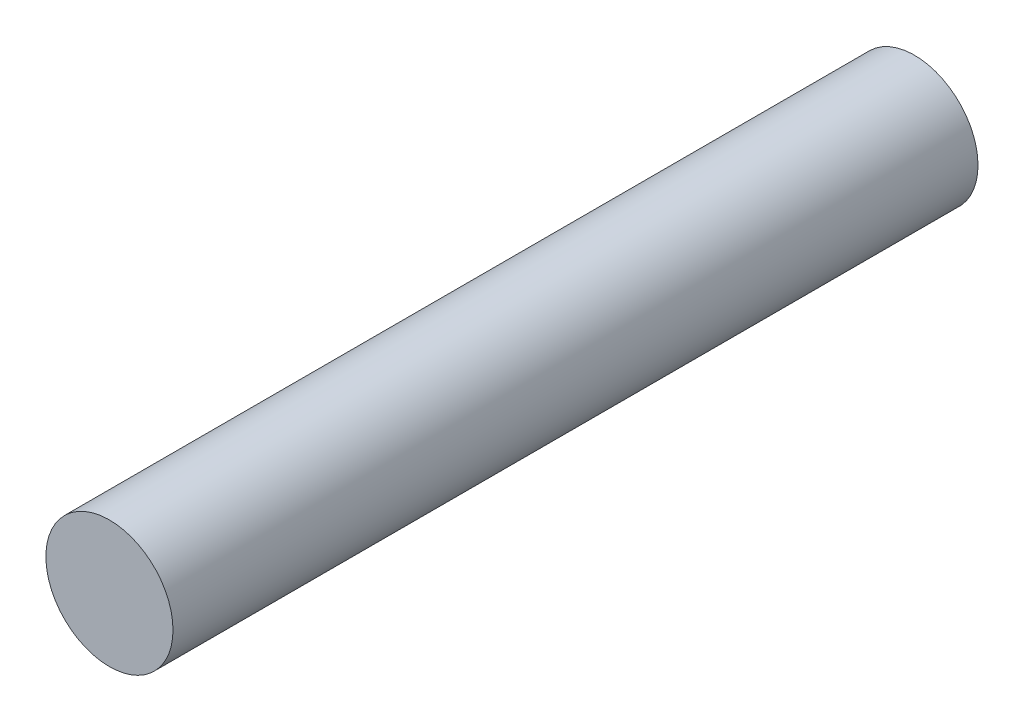
SolidWorks part; units mm, degrees
material "AISI 1020"
ref_plane "Alzado" through (0, 0, 0) normal (0, 0, 1) x (1, 0, 0)
ref_plane "Planta" through (0, 0, 0) normal (0, 1, 0) x (1, 0, 0)
ref_plane "Vista lateral" through (0, 0, 0) normal (1, 0, 0) x (0, 0, -1)
sketch "Croquis1" plane through (0, 0, 0) normal (0, 0, 1) x (1, 0, 0)
  circle A0 centre (0, 0) radius 6
  dimension "D1" = 12
extrude "Saliente-Extruir1" add sketch "Croquis1" along normal blind 76
